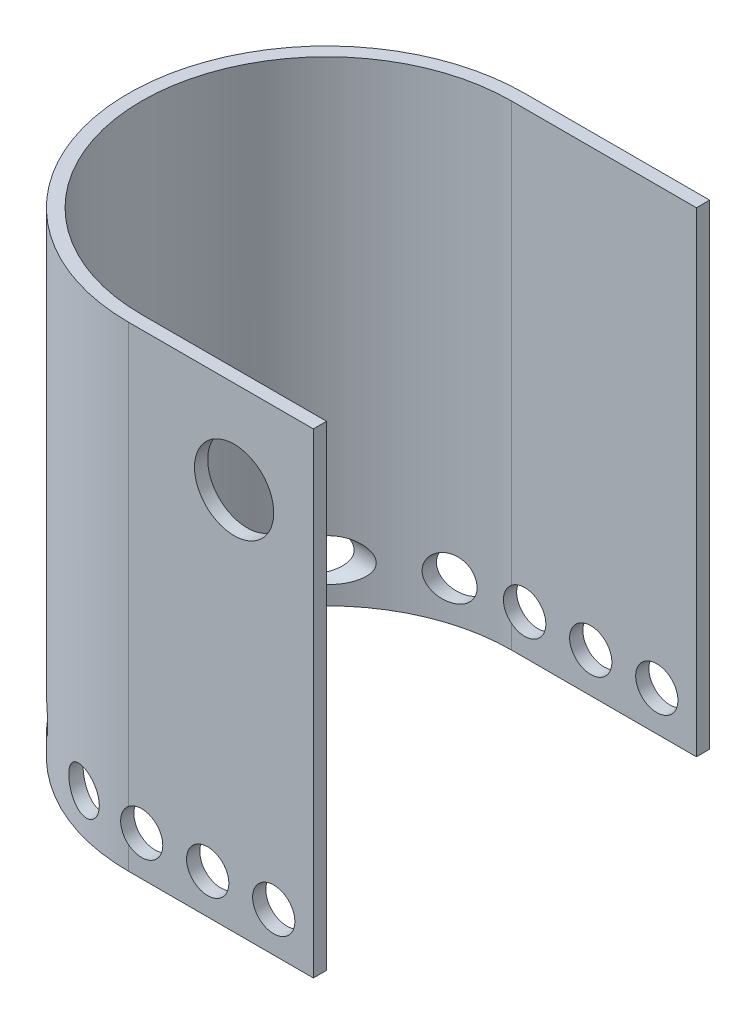
SolidWorks part; units mm, degrees
ref_plane "Front Plane" through (0, 0, 0) normal (0, 0, 1) x (1, 0, 0)
ref_plane "Top Plane" through (0, 0, 0) normal (0, 1, 0) x (1, 0, 0)
ref_plane "Right Plane" through (0, 0, 0) normal (1, 0, 0) x (0, 0, -1)
sketch "Sketch1" plane through (0, 0, 0) normal (0, 1, 0) x (1, 0, 0)
  line L11 (0, 7.5) -> (7, 7.5)
  line L13 (0, -7.5) -> (7, -7.5)
  line L15 (0, 7) -> (7, 7)
  line L16 (0, -7) -> (7, -7)
  line L17 (7, 7.5) -> (7, 7)
  line L18 (7, -7) -> (7, -7.5)
  arc A4 (0, 7.5) -> (0, -7.5) centre (0, 0) ccw
  arc A5 (0, 7) -> (0, -7) centre (0, 0) ccw
  point P4 (0, 0)
  point P6 (0, 0)
  dimension "D1" = 7
  dimension "D3" = 7.5
  dimension "D2" = 7
  dimension "D4" = 0.5
  dimension "D5" = 7
extrude "Boss-Extrude1" add sketch "Sketch1" along normal blind 18
sketch "Sketch2" plane through (0, 0, 7.5) normal (0, 0, -1) x (-1, 0, 0)
  line L0 (0, 18) -> (-7, 18) construction
  circle A0 centre (-4, 14.5) radius 1.5
  point P4 (0, 0)
  point P6 (-6.6929, 1.7347)
  point P7 (-6.6541, 0.603)
  point P14 (-6.934, -0.4591)
  point P15 (-5.5249, -0.8172)
  point P16 (-6.1339, -2.4851)
  point P17 (-6.8705, 0)
  point P19 (-1.4105, 1.5)
  point P20 (0, 0)
  point P21 (0, 0)
  dimension "D1" = 3.5
extrude "Cut-Extrude1" cut sketch "Sketch2" along normal blind 2
sketch "Sketch3" plane through (0, 0, -7.5) normal (0, 0, -1) x (-1, 0, 0)
  line L0 (-7, 18) -> (-7, 0) construction
  line L1 (-7, 0) -> (0, 0) construction
  circle A0 centre (-5.5, 1.5) radius 0.8
  circle A1 centre (-3, 1.5) radius 0.8
  circle A2 centre (-0.5, 1.5) radius 0.8
  circle A3 centre (2, 1.5) radius 0.8
  point P8 (-1.8575, 1.5)
  point P11 (0, 0)
  point P12 (-0.4939, 1.5)
  point P15 (1.9496, 1.5)
  dimension "D1" = 1.5
  dimension "D3" = 2.5
  dimension "D2" = 1.5
  dimension "D4" = 2.5
  dimension "D5" = 2.5
extrude "Cut-Extrude2" cut sketch "Sketch3" against normal through all
sketch "Sketch4" plane through (0, 0, 0) normal (1, 0, 0) x (0, 0, -1)
  line L0 (-7, 0) -> (7, 0) construction
  circle A0 centre (0, 1.5) radius 0.8
  circle A1 centre (2.5, 1.5) radius 0.8
  circle A2 centre (5, 1.5) radius 0.8
  circle A3 centre (-2.5, 1.5) radius 0.8
  circle A4 centre (-5, 1.5) radius 0.8
  point P4 (0, 1.5)
  point P6 (0.0323, 1.3709)
  point P8 (3.9727, 1.5)
  point P9 (0, 0)
  point P10 (2.2508, 1.5)
  point P13 (4.738, 1.5)
  point P16 (-2.505, 1.5)
  point P19 (-4.9103, 1.5)
  point P20 (0, 0)
  point P21 (0, 0)
  point P22 (0.7823, 1.3325)
  dimension "D1" = 1.5
  dimension "D2" = 2.5
  dimension "D3" = 2.5
  dimension "D4" = 2.5
  dimension "D5" = 2.5
extrude "Cut-Extrude3" cut sketch "Sketch4" against normal through all
